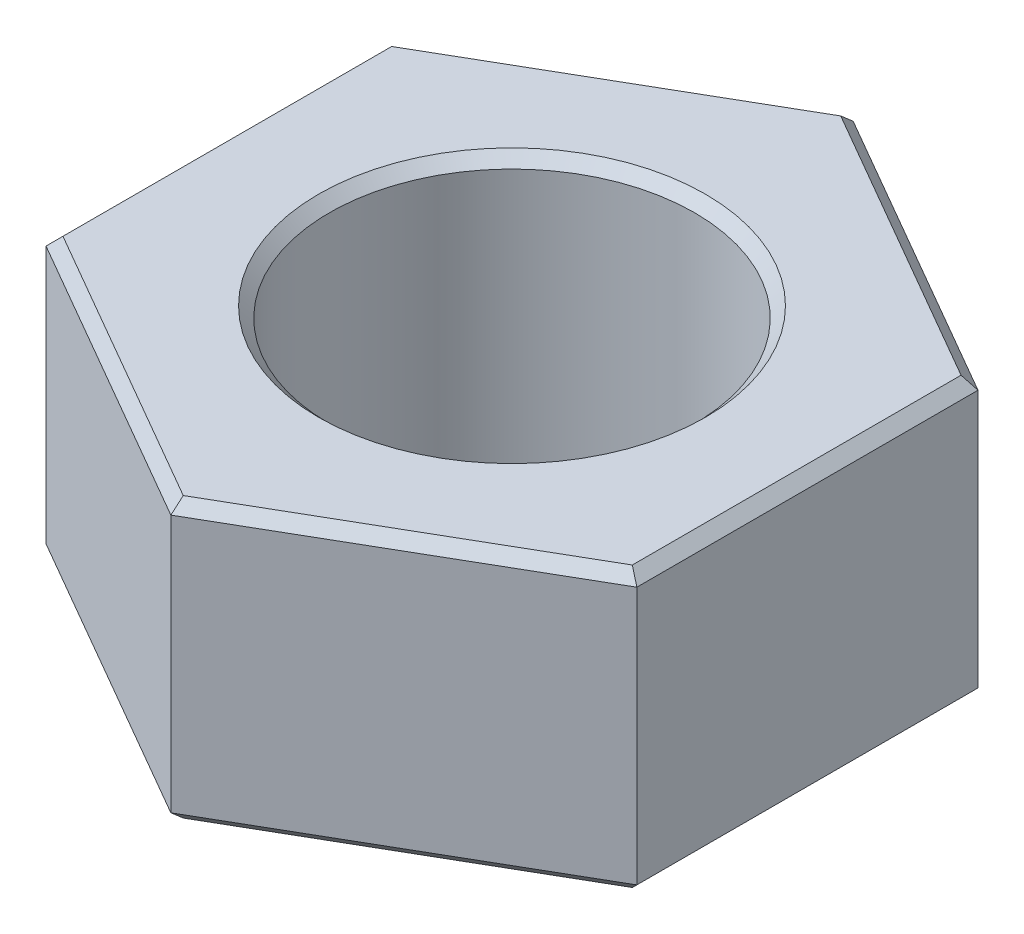
SolidWorks part; units mm, degrees
material "AISI 304"
ref_plane "Спереди" through (0, 0, 0) normal (0, 0, 1) x (1, 0, 0)
ref_plane "Сверху" through (0, 0, 0) normal (0, 1, 0) x (1, 0, 0)
ref_plane "Справа" through (0, 0, 0) normal (1, 0, 0) x (0, 0, -1)
other "Configuration Table"
sketch "Эскиз1" plane through (0, 0, 0) normal (0, 1, 0) x (1, 0, 0)
  line L0 (0, 31.7543) -> (0, 0) construction
  line L1 (0, 31.7543) -> (-27.5, 15.8771)
  line L2 (-27.5, 15.8771) -> (-27.5, -15.8771)
  line L3 (-27.5, -15.8771) -> (0, -31.7543)
  line L4 (0, -31.7543) -> (27.5, -15.8771)
  line L5 (27.5, -15.8771) -> (27.5, 15.8771)
  line L6 (27.5, 15.8771) -> (0, 31.7543)
  circle A0 centre (0, 0) radius 27.5 construction
  circle A1 centre (0, 0) radius 17
  dimension "D2" = 34
  dimension "D1" = 55
extrude "Бобышка-Вытянуть1" add sketch "Эскиз1" along normal blind 26
chamfer "Фаска1" distance 1 angle 45 14 edges at (0, 0, 17) (-13.75, 0, -23.8157) (-27.5, 0, 0) (-13.75, 0, 23.8157) (13.75, 0, 23.8157) (27.5, 0, 0) (13.75, 0, -23.8157) (0, 26, 17) (27.5, 26, 0) (13.75, 26, 23.8157) (-13.75, 26, 23.8157) (-27.5, 26, 0) (-13.75, 26, -23.8157) (13.75, 26, -23.8157)
